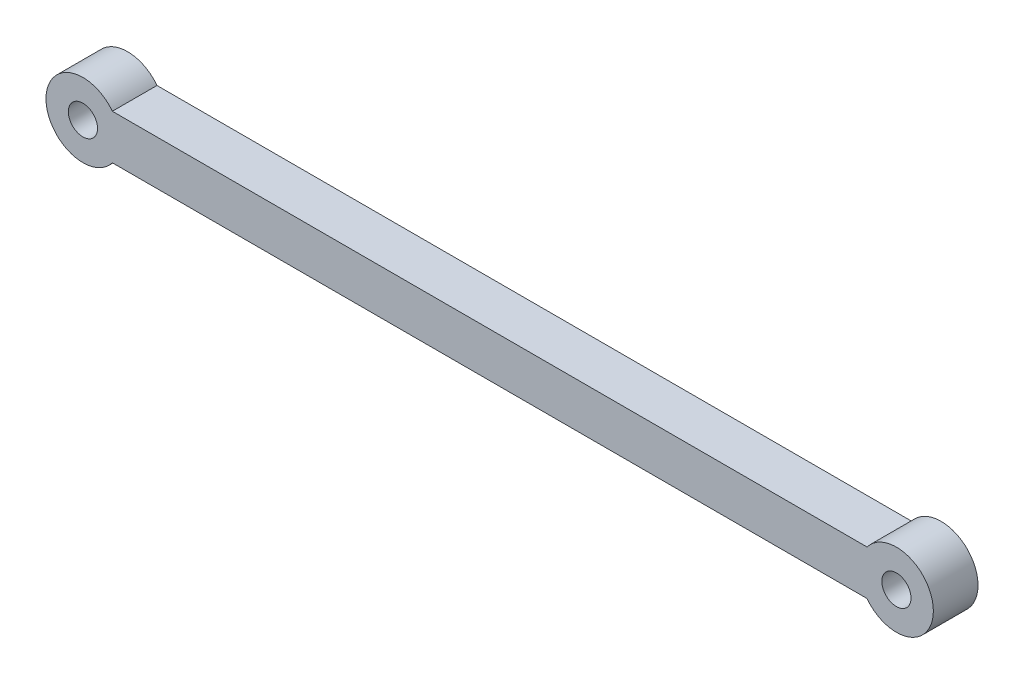
SolidWorks part; units mm, degrees
ref_plane "Front Plane" through (0, 0, 0) normal (0, 0, 1) x (1, 0, 0)
ref_plane "Top Plane" through (0, 0, 0) normal (0, 1, 0) x (1, 0, 0)
ref_plane "Right Plane" through (0, 0, 0) normal (1, 0, 0) x (0, 0, -1)
sketch "Sketch3" plane through (0, 0, 0) normal (0, 0, 1) x (1, 0, 0)
  line L0 (-625.3521, 0) -> (-225.3521, 0) construction
  line L2 (-610.8885, 10.9763) -> (-239.8157, 10.9763)
  line L3 (-610.8885, 10.9763) -> (-610.8885, -10.9763)
  line L4 (-610.8885, -10.9763) -> (-239.8157, -10.9763)
  line L5 (-239.8157, 10.9763) -> (-239.8157, -10.9763)
  circle A0 centre (-625.3521, 0) radius 18.1569
  circle A1 centre (-225.3521, 0) radius 18.1569
  point P9 (0, 0)
  point P10 (0, 0)
  dimension "D2" = 36.3139
  dimension "D1" = 400
  dimension "D3" = 21.9525
extrude "Boss-Extrude1" add sketch "Sketch3" along normal mid plane 21.9525 contours L2 L5 L4 L3 | A0 | A1
sketch "Sketch4" plane through (0, 0, 10.9763) normal (0, 0, 1) x (1, 0, 0)
  circle A0 centre (-625.3521, 0) radius 7.1807
  circle A1 centre (-225.3521, 0) radius 7.1807
  dimension "D1" = 14.3614
extrude "Cut-Extrude1" cut sketch "Sketch4" against normal through all
